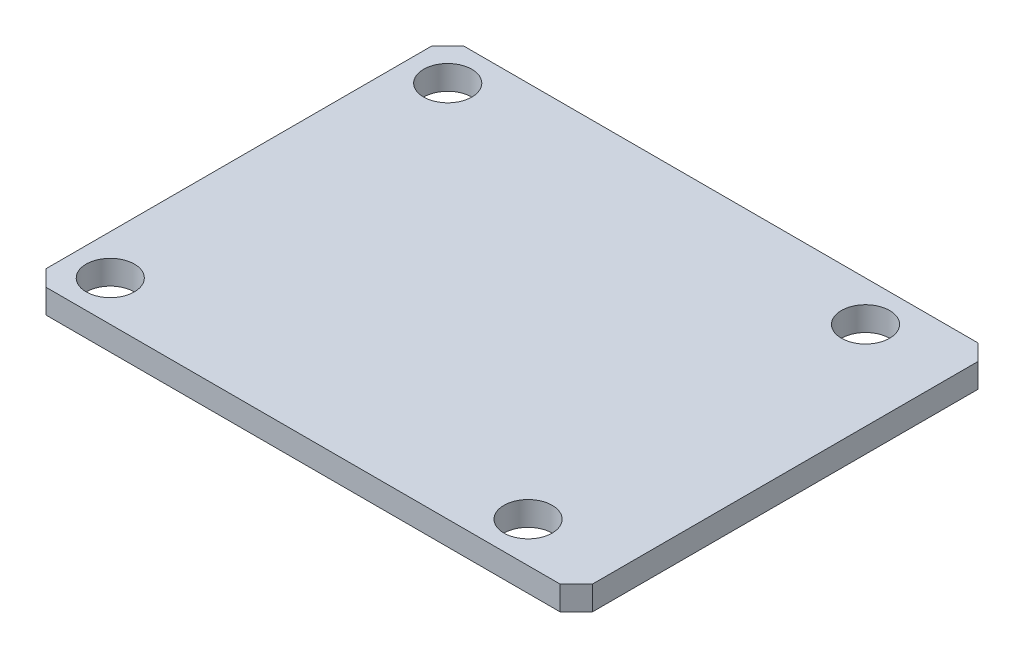
SolidWorks part; units mm, degrees
ref_plane "Front Plane" through (0, 0, 0) normal (0, 0, 1) x (1, 0, 0)
ref_plane "Top Plane" through (0, 0, 0) normal (0, 1, 0) x (1, 0, 0)
ref_plane "Right Plane" through (0, 0, 0) normal (1, 0, 0) x (0, 0, -1)
sketch "Sketch1" plane through (0, 0, 0) normal (0, 1, 0) x (1, 0, 0)
  line L1 (-17, -13) -> (17, -13)
  line L2 (-17, -13) -> (-17, 13)
  line L3 (-17, 13) -> (17, 13)
  line L4 (17, -13) -> (17, 13)
  line L5 (-17, -13) -> (17, 13) construction
  line L6 (-17, 13) -> (17, -13) construction
  point P0 (0, 0)
  dimension "D1" = 34
  dimension "D2" = 26
extrude "Boss-Extrude1" add sketch "Sketch1" along normal blind 1.5
sketch "Sketch2" plane through (0, 1.5, 0) normal (0, 1, 0) x (1, 0, 0)
  line L0 (17, 13) -> (-17, 13) construction
  line L1 (-17, 13) -> (-17, -13) construction
  circle A0 centre (-14.5, 10.5) radius 1.5
  circle A1 centre (11.5, 10.5) radius 1.5
  circle A2 centre (11.5, -10.5) radius 1.5
  circle A3 centre (-14.5, -10.5) radius 1.5
  dimension "D1" = 2.5
  dimension "D2" = 2.5
  dimension "D3" = 3
  dimension "D4" = 2
  dimension "D5" = 2
extrude "Cut-Extrude1" cut sketch "Sketch2" against normal blind 1.5
chamfer "Chamfer1" distance 1 angle 45 4 edges at (-17, 0.75, -13) (17, 0.75, -13) (17, 0.75, 13) (-17, 0.75, 13)
